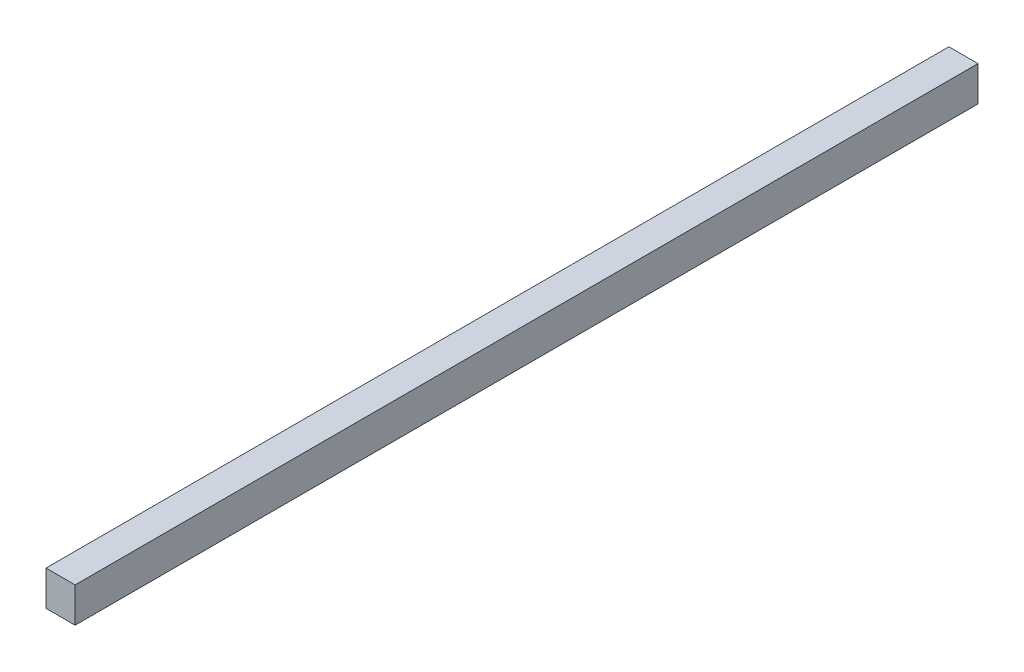
SolidWorks part; units mm, degrees
ref_plane "Front Plane" through (0, 0, 0) normal (0, 0, 1) x (1, 0, 0)
ref_plane "Top Plane" through (0, 0, 0) normal (0, 1, 0) x (1, 0, 0)
ref_plane "Right Plane" through (0, 0, 0) normal (1, 0, 0) x (0, 0, -1)
sketch "Sketch2" plane through (0, 0, 0) normal (0, 0, 1) x (1, 0, 0)
  line L1 (-7.5, -9) -> (7.5, -9)
  line L2 (-7.5, -9) -> (-7.5, 9)
  line L3 (-7.5, 9) -> (7.5, 9)
  line L4 (7.5, -9) -> (7.5, 9)
  line L5 (0, 9) -> (0, -9) construction
  line L6 (-7.5, 0) -> (7.5, 0) construction
  point P0 (0, 0)
  dimension "D1" = 18
  dimension "D2" = 15
extrude "Boss-Extrude1" add sketch "Sketch2" along normal blind 465
